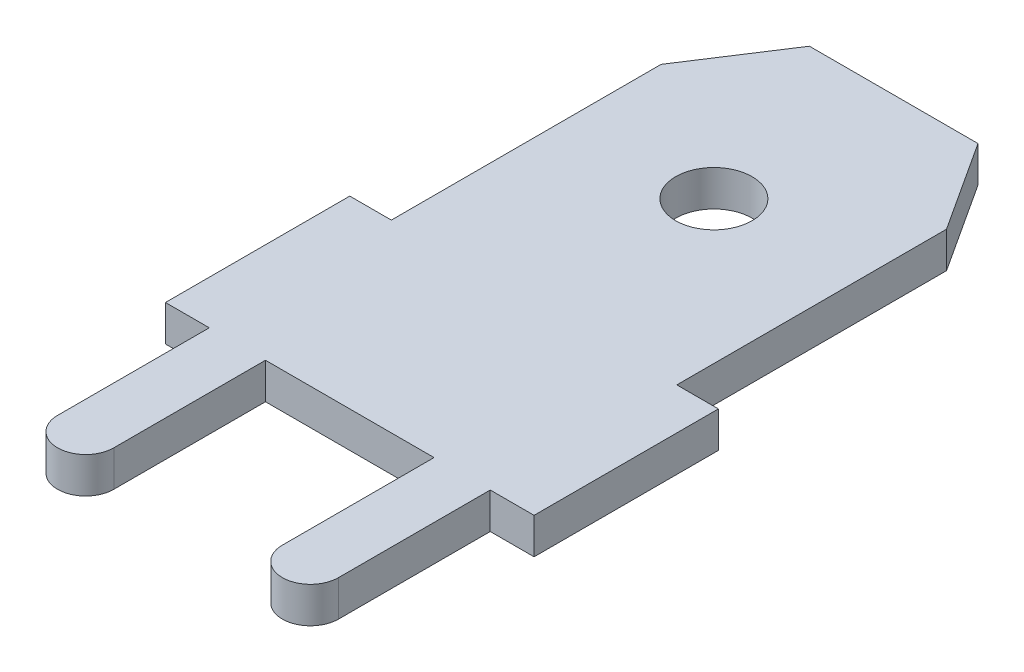
SolidWorks part; units mm, degrees
material "Brass"
ref_plane "Front Plane" through (0, 0, 0) normal (0, 0, 1) x (1, 0, 0)
ref_plane "Top Plane" through (0, 0, 0) normal (0, 1, 0) x (1, 0, 0)
ref_plane "Right Plane" through (0, 0, 0) normal (1, 0, 0) x (0, 0, -1)
sketch "Sketch1" plane through (0, 0, 0) normal (0, 1, 0) x (1, 0, 0)
  line L0 (0, 10.6539) -> (0, -8.89) construction
  line L1 (-3.175, 6) -> (-3.175, 0)
  line L2 (-3.175, 0) -> (-4.1, 0)
  line L3 (-4.1, 0) -> (-4.1, -4.1)
  line L4 (-4.1, -4.1) -> (-3.125, -4.1)
  line L5 (-3.175, 6) -> (-1.875, 8)
  line L6 (-1.875, 8) -> (1.875, 8)
  line L7 (-3.125, -4.1) -> (-3.125, -7.475)
  line L8 (-1.875, -4.1) -> (-1.875, -7.475)
  line L9 (-2.5, -8.1) -> (-3.9544, -8.1) construction
  line L10 (-3.125, -4.1) -> (-1.875, -4.1) construction
  line L11 (-1.875, -4.1) -> (1.875, -4.1)
  line L12 (1.875, -4.1) -> (1.875, -7.475)
  line L13 (3.125, -4.1) -> (3.125, -7.475)
  line L14 (4.1, -4.1) -> (3.125, -4.1)
  line L15 (4.1, 0) -> (4.1, -4.1)
  line L16 (3.175, 0) -> (4.1, 0)
  line L17 (3.175, 6) -> (3.175, 0)
  line L18 (3.175, 6) -> (1.875, 8)
  arc A0 (-3.125, -7.475) -> (-1.875, -7.475) centre (-2.5, -7.475) ccw
  circle A1 centre (0, 4) radius 0.85
  arc A2 (3.125, -7.475) -> (1.875, -7.475) centre (2.5, -7.475) cw
  point P19 (-3.175, 5.7023)
  point P20 (0, 0)
  point P21 (0, 0)
  point P22 (0, 0)
  point P23 (0, 3.7066)
  point P25 (0, -4.1)
  point P34 (0, 8)
  dimension "D1" = 6.35
  dimension "D2" = 1.7
  dimension "D3" = 8
  dimension "D4" = 8.2
  dimension "D5" = 1.25
  dimension "D6" = 4
  dimension "D7" = 16.1
  dimension "D8" = 2
  dimension "D9" = 5
  dimension "D10" = 4
extrude "Boss-Extrude1" add sketch "Sketch1" along normal mid plane 0.8
